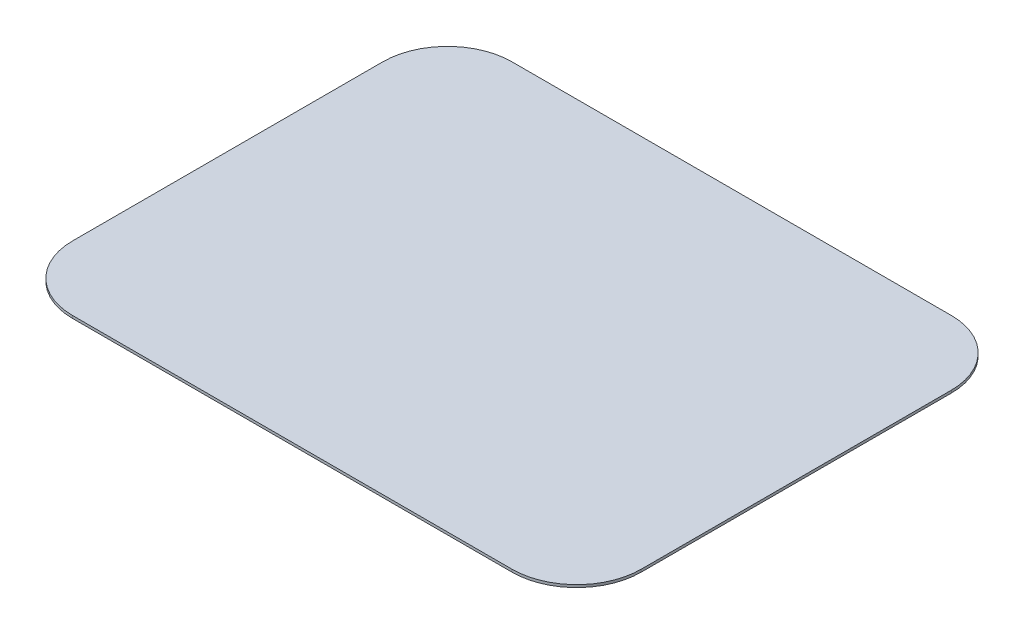
SolidWorks part; units mm, degrees
ref_plane "Front Plane" through (0, 0, 0) normal (0, 0, 1) x (1, 0, 0)
ref_plane "Top Plane" through (0, 0, 0) normal (0, 1, 0) x (1, 0, 0)
ref_plane "Right Plane" through (0, 0, 0) normal (1, 0, 0) x (0, 0, -1)
sketch "BaseS" plane through (0, 0, 0) normal (0, 1, 0) x (1, 0, 0)
  line L1 (-17, 17) -> (17, 17)
  line L2 (-22, 12) -> (-22, -12)
  line L3 (-17, -17) -> (17, -17)
  line L4 (22, 12) -> (22, -12)
  line L5 (-22, 17) -> (22, -17) construction
  line L6 (-22, -17) -> (22, 17) construction
  arc A0 (-22, -12) -> (-17, -17) centre (-17, -12) ccw
  arc A1 (17, -17) -> (22, -12) centre (17, -12) ccw
  arc A2 (22, 12) -> (17, 17) centre (17, 12) ccw
  arc A3 (-17, 17) -> (-22, 12) centre (-17, 12) ccw
  point P0 (0, 0)
  dimension "Radius" = 5
  dimension "Length" = 44
  dimension "Width" = 34
extrude "Base" add sketch "BaseS" against normal blind 0.2
